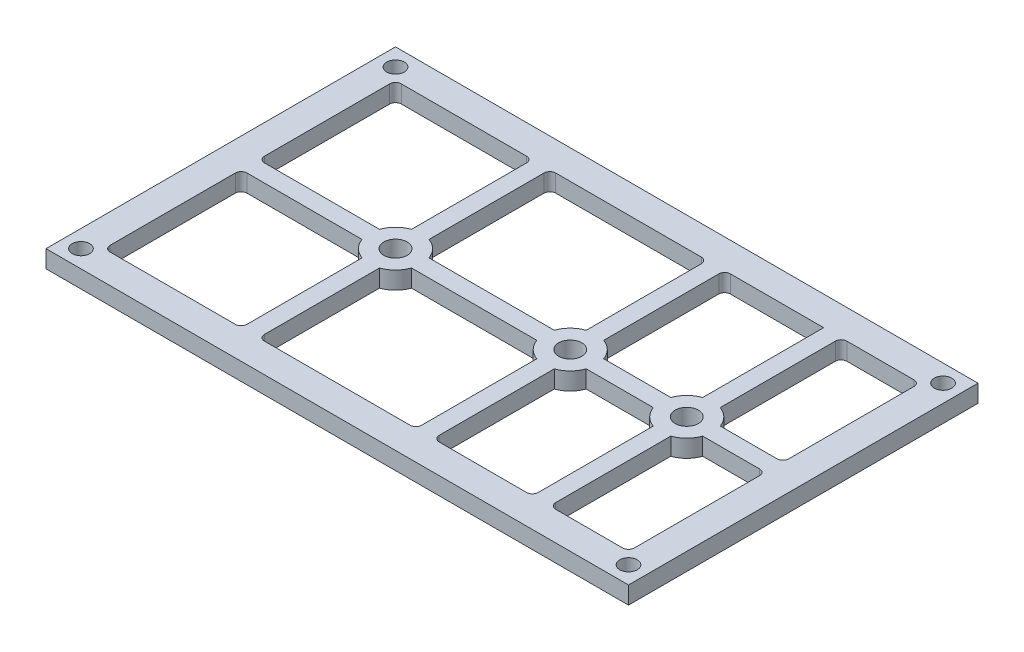
SolidWorks part; units mm, degrees
ref_plane "Front Plane" through (0, 0, 0) normal (0, 0, 1) x (1, 0, 0)
ref_plane "Top Plane" through (0, 0, 0) normal (0, 1, 0) x (1, 0, 0)
ref_plane "Right Plane" through (0, 0, 0) normal (1, 0, 0) x (0, 0, -1)
sketch "Sketch1" plane through (0, 0, 0) normal (0, 1, 0) x (1, 0, 0)
  line L1 (-50, 30) -> (50, 30)
  line L2 (-50, 30) -> (-50, -30)
  line L3 (-50, -30) -> (50, -30)
  line L4 (50, 30) -> (50, -30)
  line L5 (-50, 30) -> (50, -30) construction
  line L6 (-50, -30) -> (50, 30) construction
  point P0 (0, 0)
  dimension "D1" = 60
  dimension "D2" = 100
extrude "Boss-Extrude1" add sketch "Sketch1" along normal blind 3
sketch "Sketch2" plane through (0, 3, 0) normal (0, 1, 0) x (1, 0, 0)
  line L0 (-50, 30) -> (-50, -30) construction
  line L1 (-50, -30) -> (50, -30) construction
  line L2 (-45, -25) -> (-21.5, -25)
  line L3 (-45, -25) -> (-45, -1.5)
  line L4 (-45, -1.5) -> (-24.2426, -1.5)
  line L5 (-21.5, -25) -> (-21.5, -4.2426)
  line L6 (-24.2426, 1.5) -> (-45, 1.5)
  line L7 (-21.5, 4.2426) -> (-21.5, 25)
  line L8 (-21.5, 25) -> (-45, 25)
  line L9 (-45, 1.5) -> (-45, 25)
  line L10 (50, 30) -> (-50, 30) construction
  line L11 (50, -30) -> (50, 30) construction
  line L12 (-15.7574, 1.5) -> (5.7574, 1.5)
  line L13 (-18.5, 4.2426) -> (-18.5, 25)
  line L14 (-18.5, 25) -> (8.5, 25)
  line L15 (8.5, 4.2426) -> (8.5, 25)
  line L16 (-15.7574, -1.5) -> (5.7574, -1.5)
  line L17 (-18.5, -4.2426) -> (-18.5, -25)
  line L18 (-18.5, -25) -> (8.5, -25)
  line L19 (8.5, -4.2426) -> (8.5, -25)
  line L20 (14.2426, -1.5) -> (25.7574, -1.5)
  line L21 (11.5, -4.2426) -> (11.5, -25)
  line L22 (11.5, -25) -> (28.5, -25)
  line L23 (28.5, -4.2426) -> (28.5, -25)
  line L24 (14.2426, 1.5) -> (25.7574, 1.5)
  line L25 (11.5, 4.2426) -> (11.5, 25)
  line L26 (11.5, 25) -> (28.5, 25)
  line L27 (28.5, 4.2426) -> (28.5, 25)
  line L28 (34.2426, 1.5) -> (45, 1.5)
  line L29 (31.5, 4.2426) -> (31.5, 25)
  line L30 (31.5, 25) -> (45, 25)
  line L31 (45, 1.5) -> (45, 25)
  line L32 (34.2426, -1.5) -> (45, -1.5)
  line L33 (31.5, -4.2426) -> (31.5, -25)
  line L34 (31.5, -25) -> (45, -25)
  line L35 (45, -1.5) -> (45, -25)
  line L36 (-21.5, 14.6213) -> (-18.5, 14.6213) construction
  line L37 (8.5, 14.6213) -> (11.5, 14.6213) construction
  line L38 (28.5, 14.6213) -> (31.5, 14.6213) construction
  circle A0 centre (-20, 0) radius 2
  circle A1 centre (10, 0) radius 2
  circle A2 centre (30, 0) radius 2
  circle A3 centre (-20, 0) radius 4.5
  circle A4 centre (10, 0) radius 4.5
  circle A5 centre (30, 0) radius 4.5
  circle A6 centre (47, -27) radius 1.5
  circle A7 centre (-47, -27) radius 1.5
  circle A8 centre (-47, 27) radius 1.5
  circle A9 centre (47, 27) radius 1.5
  point P48 (-20, 14.6213)
  dimension "D2" = 4
  dimension "D5" = 9
  dimension "D12" = 3
  dimension "D1" = 30
  dimension "D3" = 20
  dimension "D4" = 30
  dimension "D6" = 5
  dimension "D7" = 5
  dimension "D8" = 5
  dimension "D9" = 3
  dimension "D10" = 5
  dimension "D11" = 3
  dimension "D13" = 3
  dimension "D14" = 3
  dimension "D15" = 3
  dimension "D16" = 3
extrude "Cut-Extrude1" cut sketch "Sketch2" against normal through all contours A3 L7 L8 L9 L6 | A3 L4 L3 L2 L5 | A4 L15 L14 L13 A3 L12 | A4 L16 A3 L17 L18 L19 | A5 L20 A4 L21 L22 L23 | A5 L27 L26 L25 A4 L24 | A5 L28 L31 L30 L29 | A5 L33 L34 L35 L32 | A2 | A1 | A0 | A7 | A8 | A6 | A9
fillet "Fillet1" radius 1 19 edges at (-45, 1.5, -1.5) (-45, 1.5, 1.5) (45, 1.5, 1.5) (45, 1.5, 25) (45, 1.5, -1.5) (45, 1.5, -25) (31.5, 1.5, -25) (11.5, 1.5, -25) (28.5, 1.5, 25) (31.5, 1.5, 25) (11.5, 1.5, 25) (8.5, 1.5, 25) (-18.5, 1.5, 25) (-18.5, 1.5, -25) (8.5, 1.5, -25) (-21.5, 1.5, -25) (-21.5, 1.5, 25) (-45, 1.5, 25) (-45, 1.5, -25)
